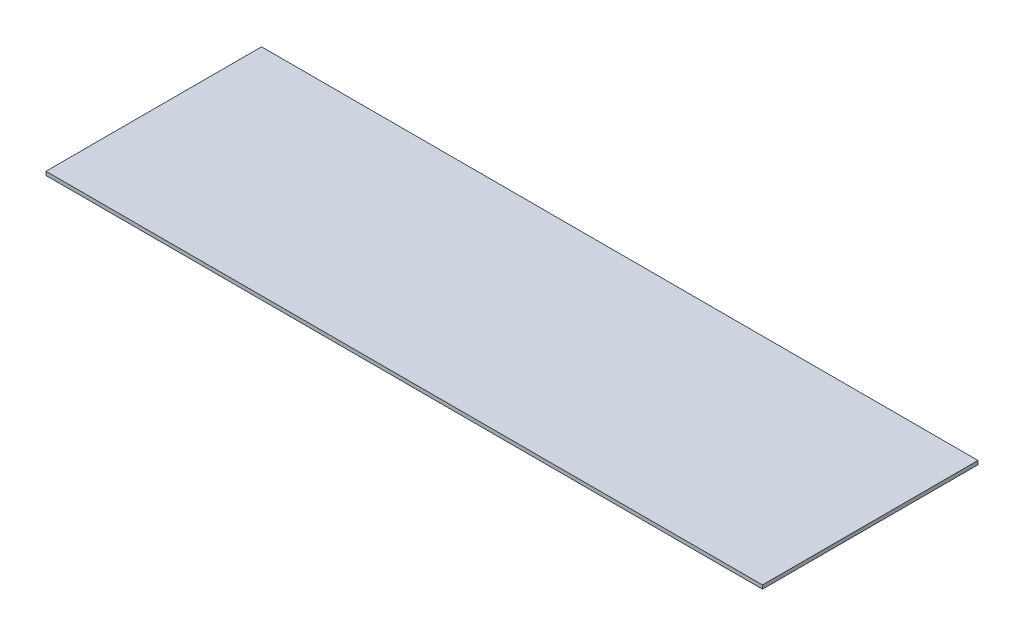
SolidWorks part; units mm, degrees
material "PC High Viscosity"
ref_plane "Front Plane" through (0, 0, 0) normal (0, 0, 1) x (1, 0, 0)
ref_plane "Top Plane" through (0, 0, 0) normal (0, 1, 0) x (1, 0, 0)
ref_plane "Right Plane" through (0, 0, 0) normal (1, 0, 0) x (0, 0, -1)
sketch "Sketch1" plane through (0, 0, 0) normal (0, 1, 0) x (1, 0, 0)
  line L1 (0, 0) -> (1219.2, 0)
  line L2 (0, 0) -> (0, 366.776)
  line L3 (0, 366.776) -> (1219.2, 366.776)
  line L4 (1219.2, 0) -> (1219.2, 366.776)
  dimension "D1" = 366.776
  dimension "D2" = 1219.2
extrude "Boss-Extrude1" add sketch "Sketch1" along normal blind 6.35
sketch "Sketch4" plane through (0, 6.35, 0) normal (0, 1, 0) x (1, 0, 0)
  line L0 (1219.2, 0) -> (1219.2, 366.776) construction
  line L1 (0, 366.776) -> (1219.2, 366.776)
  line L2 (0, 366.776) -> (0, 360.426)
  line L3 (0, 360.426) -> (1219.2, 360.426)
  line L4 (1219.2, 366.776) -> (1219.2, 360.426)
  dimension "D1" = 6.35
